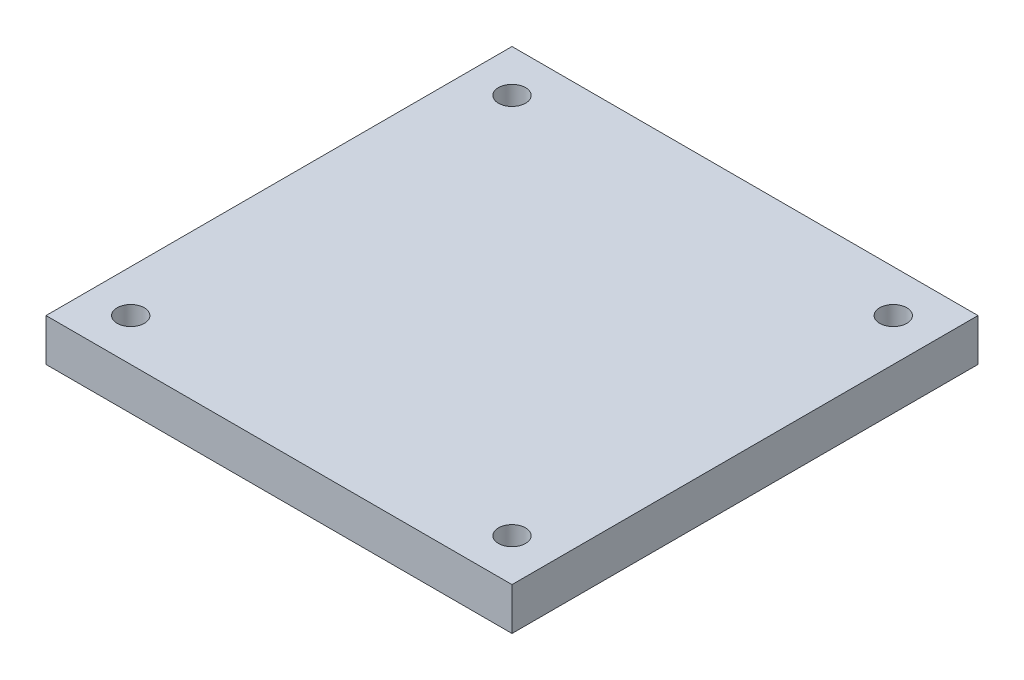
SolidWorks part; units mm, degrees
material "Pure Gold"
ref_plane "Front Plane" through (0, 0, 0) normal (0, 0, 1) x (1, 0, 0)
ref_plane "Top Plane" through (0, 0, 0) normal (0, 1, 0) x (1, 0, 0)
ref_plane "Right Plane" through (0, 0, 0) normal (1, 0, 0) x (0, 0, -1)
sketch "Sketch1" plane through (0, 0, 0) normal (0, 1, 0) x (1, 0, 0)
  line L1 (27.5, -27.5) -> (-27.5, -27.5)
  line L2 (27.5, -27.5) -> (27.5, 27.5)
  line L3 (27.5, 27.5) -> (-27.5, 27.5)
  line L4 (-27.5, -27.5) -> (-27.5, 27.5)
  line L5 (27.5, -27.5) -> (-27.5, 27.5) construction
  line L6 (27.5, 27.5) -> (-27.5, -27.5) construction
  line L7 (22.5, -22.5) -> (-22.5, -22.5) construction
  line L8 (22.5, -22.5) -> (22.5, 22.5) construction
  line L9 (22.5, 22.5) -> (-22.5, 22.5) construction
  line L10 (-22.5, -22.5) -> (-22.5, 22.5) construction
  line L11 (22.5, -22.5) -> (-22.5, 22.5) construction
  line L12 (22.5, 22.5) -> (-22.5, -22.5) construction
  point P0 (0, 0)
  point P6 (0, 0)
  dimension "D1" = 45
  dimension "D2" = 45
  dimension "D3" = 55
extrude "Boss-Extrude1" add sketch "Sketch1" along normal blind 5
sketch "Sketch2" plane through (0, 0, 0) normal (0, -1, 0) x (1, 0, 0)
  circle A0 centre (-22.5, 22.5) radius 1.6
  circle A1 centre (22.5, 22.5) radius 1.6
  circle A2 centre (22.5, -22.5) radius 1.6
  circle A3 centre (-22.5, -22.5) radius 1.6
  dimension "D1" = 3.2
extrude "Cut-Extrude1" cut sketch "Sketch2" against normal blind 5
